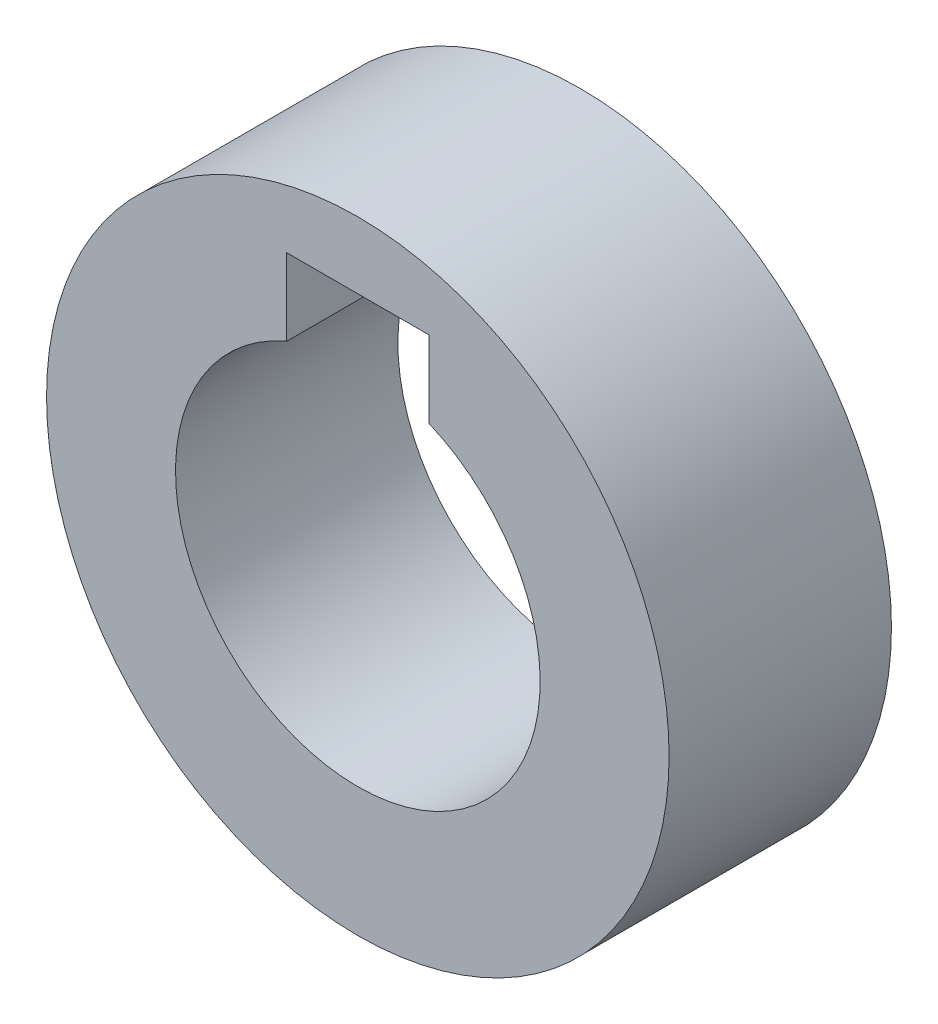
SolidWorks part; units mm, degrees
ref_plane "Front Plane" through (0, 0, 0) normal (0, 0, 1) x (1, 0, 0)
ref_plane "Top Plane" through (0, 0, 0) normal (0, 1, 0) x (1, 0, 0)
ref_plane "Right Plane" through (0, 0, 0) normal (1, 0, 0) x (0, 0, -1)
sketch "Sketch1" plane through (0, 0, 0) normal (0, 0, 1) x (1, 0, 0)
  line L0 (-1.6, 3.7749) -> (-1.6, 5.5)
  line L1 (-1.6, 5.5) -> (1.6, 5.5)
  line L2 (1.6, 5.5) -> (1.6, 3.7749)
  line L3 (0, 0) -> (0, 7) construction
  circle A0 centre (0, 0) radius 4.1 construction
  circle A1 centre (0, 0) radius 7
  arc A2 (-1.6, 3.7749) -> (1.6, 3.7749) centre (0, 0) ccw
  dimension "D1" = 8.2
  dimension "D2" = 14
  dimension "D3" = 3.2
  dimension "D4" = 5.5
extrude "Boss-Extrude1" add sketch "Sketch1" along normal blind 5
